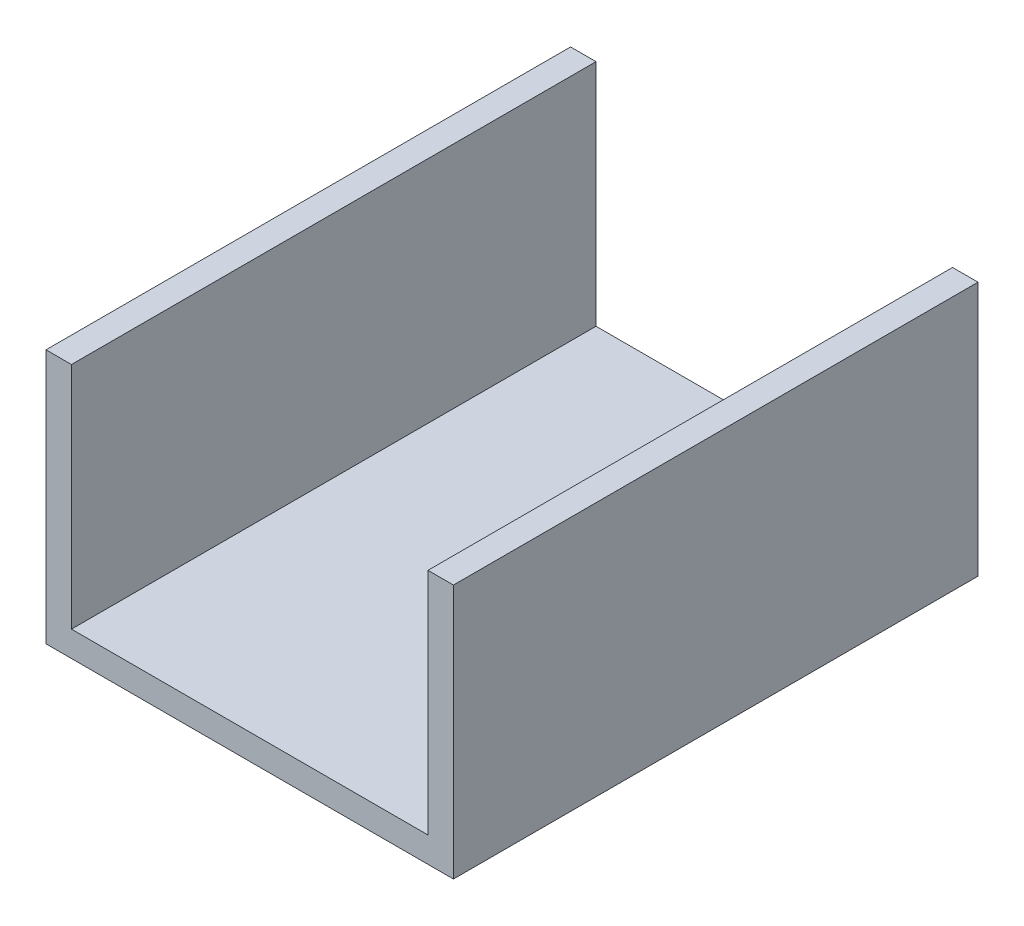
SolidWorks part; units mm, degrees
ref_plane "Ön Düzlem" through (0, 0, 0) normal (0, 0, 1) x (1, 0, 0)
ref_plane "Üst Düzlem" through (0, 0, 0) normal (0, 1, 0) x (1, 0, 0)
ref_plane "Sağ Düzlem" through (0, 0, 0) normal (1, 0, 0) x (0, 0, -1)
sketch "Çizim1" plane through (0, 0, 0) normal (0, 0, 1) x (1, 0, 0)
  line L0 (0, 0) -> (80, 0)
  line L1 (0, 0) -> (0, 50)
  line L2 (0, 50) -> (5, 50)
  line L3 (5, 50) -> (5, 5)
  line L4 (5, 5) -> (75, 5)
  line L5 (80, 0) -> (80, 50)
  line L6 (80, 50) -> (75, 50)
  line L7 (75, 50) -> (75, 5)
  dimension "D1" = 50
  dimension "D2" = 80
  dimension "D3" = 5
  dimension "D4" = 45
  dimension "D5" = 70
extrude "Yükseklik-Ekstrüzyon1" add sketch "Çizim1" along normal blind 103
